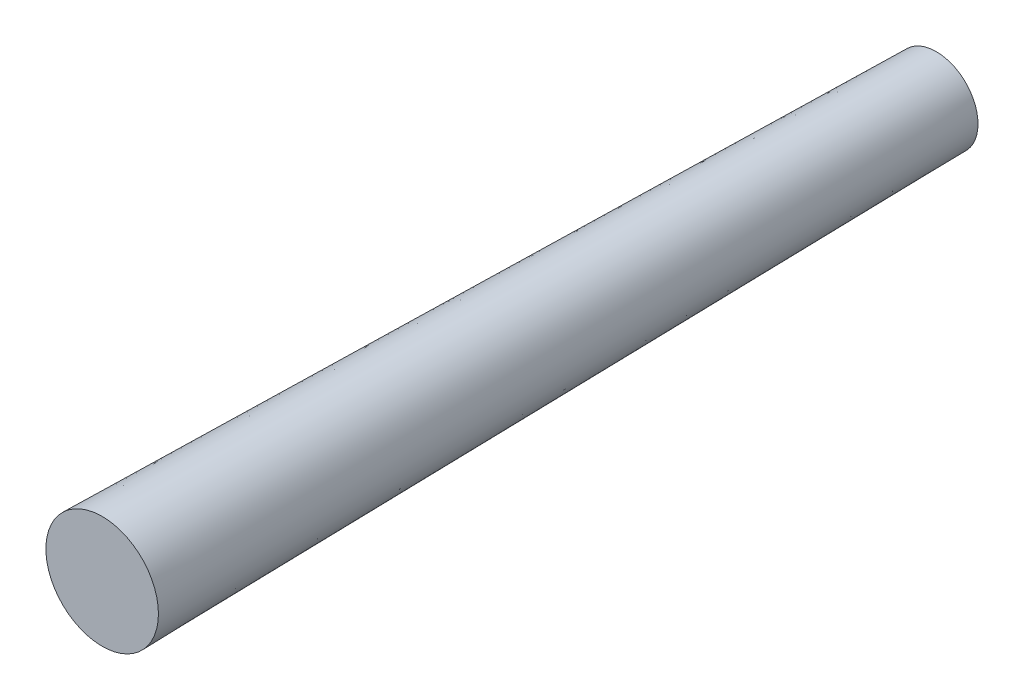
SolidWorks part; units mm, degrees
ref_plane "Front Plane" through (0, 0, 0) normal (0, 0, 1) x (1, 0, 0)
ref_plane "Top Plane" through (0, 0, 0) normal (0, 1, 0) x (1, 0, 0)
ref_plane "Right Plane" through (0, 0, 0) normal (1, 0, 0) x (0, 0, -1)
sketch "Sketch1" plane through (0, 0, 0) normal (0, 0, 1) x (1, 0, 0)
  line L0 (0, 78.349) -> (0, -87.9312) construction
  line L1 (-94.4133, 0) -> (86.2402, 0) construction
  circle A0 centre (0, 0) radius 3
  dimension "D1" = 6
extrude "Boss-Extrude3" add sketch "Sketch1" along normal blind 60 contours A0
draft "Draft2" type of draft neutral plane draft angle 1 faces to draft 1 face at (3, 0, 60) neutral plane through (0, 0, 0) neutral plane normal (0, 0, -1) parameters "D1"=1
